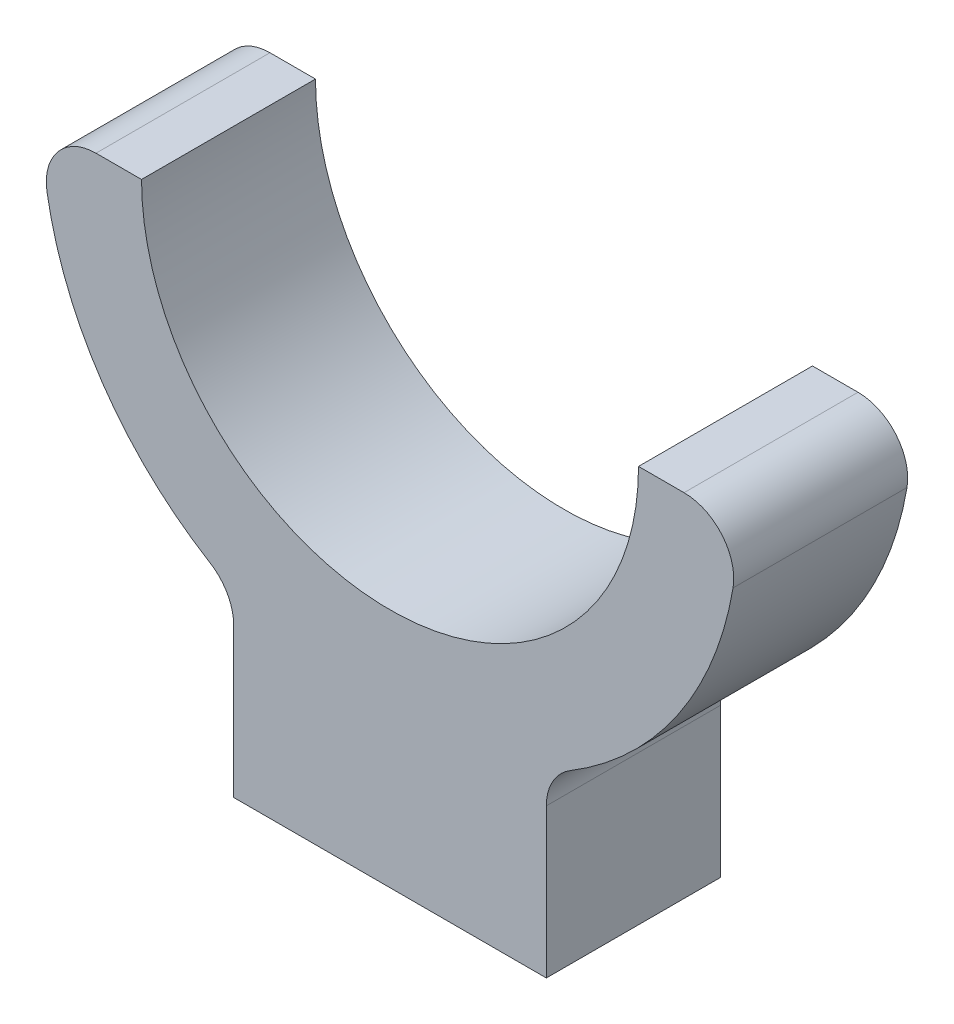
SolidWorks part; units mm, degrees
ref_plane "前视基准面" through (0, 0, 0) normal (0, 0, 1) x (1, 0, 0)
ref_plane "上视基准面" through (0, 0, 0) normal (0, 1, 0) x (1, 0, 0)
ref_plane "右视基准面" through (0, 0, 0) normal (1, 0, 0) x (0, 0, -1)
sketch "草图1" plane through (0, 0, 0) normal (0, 0, 1) x (1, 0, 0)
  line L0 (-15.0268, 0) -> (-12.7, 0)
  line L1 (12.7, 0) -> (15.0268, 0)
  line L3 (-7.9892, -17.3792) -> (-7.9892, -24.9992)
  line L4 (-7.9892, -24.9992) -> (7.9892, -24.9992)
  line L5 (7.9892, -17.3792) -> (7.9892, -24.9992)
  arc A0 (-12.7, 0) -> (12.7, 0) centre (0, 0) ccw
  arc A1 (-17.5313, -2.9633) -> (-9.2131, -15.2068) centre (0, 0) ccw
  arc A2 (9.2131, -15.2068) -> (17.5313, -2.9633) centre (0, 0) ccw
  circle A3 centre (0, 0) radius 17.78 construction
  circle A4 centre (0, 0) radius 12.7 construction
  arc A5 (-17.5313, -2.9633) -> (-15.0268, 0) centre (-15.0268, -2.54) cw
  arc A6 (17.5313, -2.9633) -> (15.0268, 0) centre (15.0268, -2.54) ccw
  arc A7 (7.9892, -17.3792) -> (9.2131, -15.2068) centre (10.5292, -17.3792) cw
  arc A8 (-7.9892, -17.3792) -> (-9.2131, -15.2068) centre (-10.5292, -17.3792) ccw
  point P6 (14.3446, 4.3856)
  point P10 (0, -24.9992)
  point P11 (20.08, 0)
  dimension "D1" = 25.4
  dimension "D3" = 2.54
  dimension "D4" = 2.54
  dimension "D5" = 2.54
  dimension "D6" = 2.54
  dimension "D7" = 7.62
  dimension "D8" = 15.9784
  dimension "D2" = 5.08
extrude "凸台-拉伸1" add sketch "草图1" along normal blind 8.89
